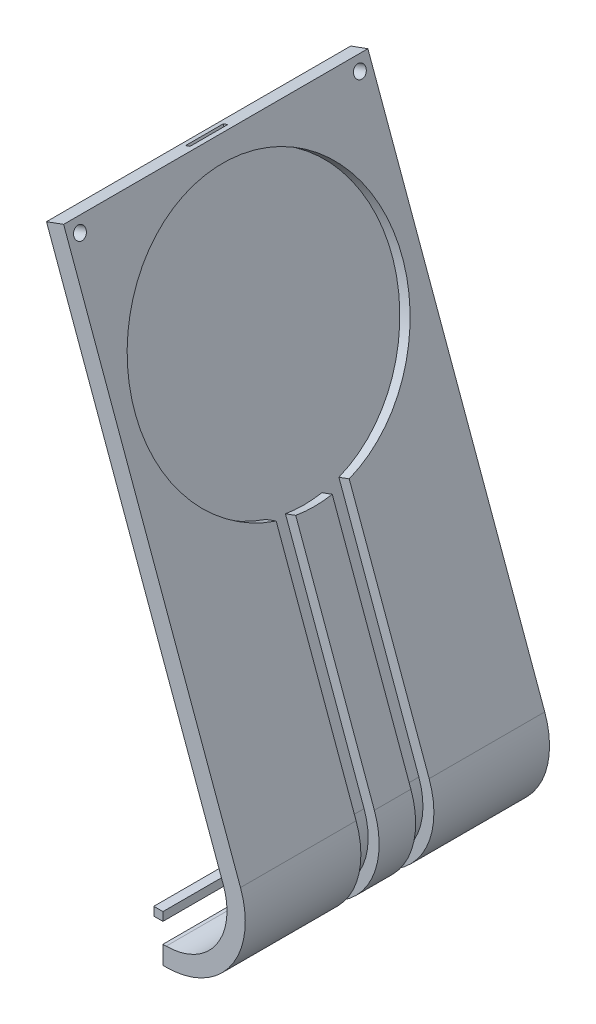
SolidWorks part; units mm, degrees
material "PLA"
ref_plane "前视基准面" through (0, 0, 0) normal (0, 0, 1) x (1, 0, 0)
ref_plane "上视基准面" through (0, 0, 0) normal (0, 1, 0) x (1, 0, 0)
ref_plane "右视基准面" through (0, 0, 0) normal (1, 0, 0) x (0, 0, -1)
other "Configuration Table"
sketch "草图2" plane through (0, 0, 0) normal (0, 0, 1) x (1, 0, 0)
  line L5 (40.3995, 18.4699) -> (11.3351, 98.3236)
  line L7 (13.6945, 105.2907) -> (9.3719, 103.7174) construction
  line L8 (9.3719, 103.7174) -> (40.3995, 18.4699) construction
  line L11 (-44.8208, 5.0497) -> (31.0025, 5.0497) construction
  line L12 (31.0025, 5.0497) -> (30.4692, 5.0497)
  line L13 (27.4692, 3.0497) -> (27.4692, 5.0497) construction
  arc A0 (31.0025, 5.0497) -> (40.3995, 18.4699) centre (31.0025, 15.0497) ccw
  arc A1 (31.0025, 5.0497) -> (40.3995, 18.4699) centre (31.0025, 15.0497) ccw construction
  dimension "D3" = 3
  dimension "D2" = 10
  dimension "D1" = 5.74
extrude "整体拉伸-薄壁1" add sketch "草图2" along normal mid plane 50 thin
sketch "草图4" plane through (44.4288, 16.1708, 0) normal (0.9397, 0.342, 0) x (0, 0, -1)
  line L0 (-25, 88.5171) -> (25, 88.5171) construction
  circle A0 centre (0, 63.1171) radius 22
  dimension "D1" = 44
  dimension "D2" = 25.4
extrude "中间圆切除-拉伸1" cut sketch "草图4" against normal blind 1.8
sketch "草图3" plane through (0, 0, 0) normal (0, 0, 1) x (1, 0, 0)
  line L0 (43.2186, 19.4959) -> (14.1542, 99.3496) construction
  line L1 (43.2186, 19.4959) -> (14.1542, 99.3496) construction
  line L2 (30.4692, 2.0497) -> (30.4692, 5.0497) construction
  line L5 (41.5271, 18.8803) -> (28.6745, 54.1926)
  line L6 (41.5271, 18.8803) -> (12.4627, 98.734) construction
  line L7 (30.4692, 3.8624) -> (30.4692, 3.8624) construction
  line L9 (28.6745, 54.1926) -> (30.3659, 54.8082) construction
  line L16 (28.6745, 54.1926) -> (27.6484, 57.0116)
  line L17 (28.672, 3.9619) -> (19.484, 9.0229) construction
  arc A0 (31.0025, 5.0497) -> (40.3995, 18.4699) centre (31.0025, 15.0497) ccw construction
  arc A1 (19.484, 9.0229) -> (43.2186, 19.4959) centre (31.0025, 15.0497) ccw construction
  arc A2 (30.4692, 3.8624) -> (41.5271, 18.8803) centre (31.0025, 15.0497) ccw
  dimension "D2" = 3
  dimension "D1" = 1.8
extrude "线槽切除-拉伸-薄壁1" cut sketch "草图3" against normal blind 3 from offset 6 thin
mirror "镜向1" about plane through (0, 0, 0) normal (0, 0, 1) of "线槽切除-拉伸-薄壁1"
sketch "草图11" plane through (30.4692, 0, 0) normal (-1, 0, 0) x (0, 0, 1)
  line L0 (-25, 2.0497) -> (-25, 5.0497) construction
  line L1 (-25, 9.7033) -> (-6.1, 9.7033)
  line L2 (-25, 9.7033) -> (-25, 7.9924)
  line L3 (-25, 7.9924) -> (-6.1, 7.9924)
  line L4 (-6.1, 9.7033) -> (-6.1, 7.9924)
  line L6 (6.1, 9.7033) -> (25, 9.7033)
  line L7 (6.1, 9.7033) -> (6.1, 8.3033)
  line L8 (6.1, 8.3033) -> (25, 8.3033)
  line L9 (25, 9.7033) -> (25, 8.3033)
  line L11 (-6, 2.0606) -> (-6, 3.8624) construction
  line L13 (6, 2.0606) -> (6, 3.8624) construction
  dimension "D2" = 0.1
  dimension "D3" = 0.1
extrude "底部卡扣凸台-拉伸3" add sketch "草图11" along normal blind 1.5
fillet "底部卡扣圆角1" radius 0.25 4 edges at (28.9692, 9.7033, -15.55) (28.9692, 8.8479, -6.1) (28.9692, 7.9924, -15.55) (28.9692, 8.8479, -25)
sketch "草图12" plane through (41.6097, 15.1447, 0) normal (-0.9397, -0.342, 0) x (0, 0, 1)
  line L1 (25, 88.5171) -> (-25, 88.5171) construction
  line L2 (-25, 3.5386) -> (-25, 88.5171) construction
  line L3 (25, 3.5386) -> (25, 88.5171) construction
  circle A0 centre (23, 86.5171) radius 1
  circle A1 centre (-23, 86.5171) radius 1
  point P10 (0, 0)
  dimension "D1" = 2
  dimension "D2" = 2
  dimension "D3" = 2
  dimension "D4" = 2
  dimension "D5" = 2
  dimension "D6" = 2
extrude "螺丝孔" cut sketch "草图12" against normal through all
sketch "草图14" plane through (-30.2746, 83.1789, 0) normal (-0.342, 0.9397, 0) x (0.9397, 0.342, 0)
  line L0 (44.2802, -5.1) -> (47.2802, -5.1) construction
  line L1 (46.0802, 3.1) -> (45.2802, 3.1)
  line L2 (46.0802, 3.1) -> (46.0802, -3.1)
  line L3 (46.0802, -3.1) -> (45.2802, -3.1)
  line L4 (45.2802, 3.1) -> (45.2802, -3.1)
  line L5 (47.2802, 5.1) -> (44.2802, 5.1) construction
  line L6 (44.2802, -25) -> (44.2802, 25) construction
  line L7 (47.2802, -25) -> (47.2802, 25) construction
  dimension "D1" = 2
  dimension "D2" = 2
  dimension "D3" = 1
  dimension "D4" = 1.2
extrude "切除-拉伸2" cut sketch "草图14" against normal blind 1
